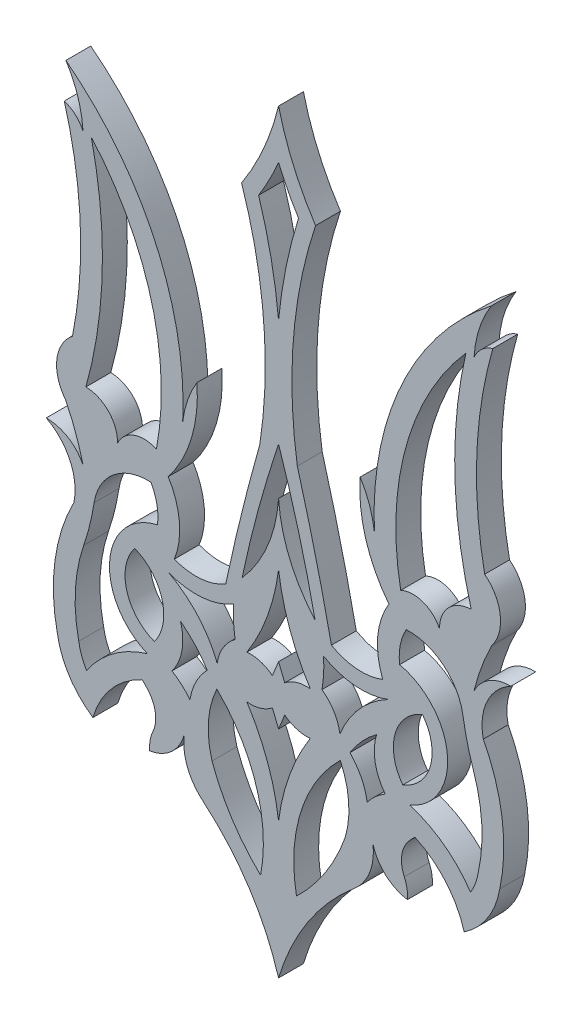
SolidWorks part; units mm, degrees
ref_plane "Спереди" through (0, 0, 0) normal (0, 0, 1) x (1, 0, 0)
ref_plane "Сверху" through (0, 0, 0) normal (0, 1, 0) x (1, 0, 0)
ref_plane "Справа" through (0, 0, 0) normal (1, 0, 0) x (0, 0, -1)
sketch "Эскиз1" plane through (0, 0, 0) normal (0, 0, 1) x (1, 0, 0)
  line L0 (0, 59.3327) -> (0, 0) construction
  line L1 (-37.3731, 0) -> (0, 0) construction
  line L2 (-37.3731, 121.4692) -> (44.9369, 121.4692) construction
  line L3 (-74.7461, 59.3327) -> (-74.7461, -26.1169) construction
  point P4 (0, 0)
  line B0 (-37.3731, 44.06) -> (-38.3679, 41.6166)
  line B1 (-36.3782, 41.6166) -> (-37.3731, 44.06)
  line B2 (-37.3731, 34.6918) -> (-36.3782, 37.1352)
  line B3 (-38.3679, 37.1352) -> (-37.3731, 34.6918)
  arc B4 (-28.8698, 50.6176) -> (-34.3536, 72.8129) centre (-358.3243, -19.0069) ccw
  arc B5 (-28.8698, 50.6176) -> (-20.6106, 49.9659) centre (-24.0648, 58.8518) ccw
  arc B6 (-19.6244, 60.9582) -> (-20.6106, 49.9659) centre (-9.1755, 54.4803) ccw
  arc B7 (-24.2373, 76.3591) -> (-19.6244, 60.9582) centre (-2.0942, 74.6002) ccw
  arc B8 (-21.9542, 69.7913) -> (-24.2373, 76.3591) centre (-38.2708, 67.8) ccw
  arc B9 (-3.1675, 110.7233) -> (-21.9542, 69.7913) centre (26.7273, 72.2251) ccw
  arc B10 (-3.1675, 110.7233) -> (-5.9306, 102.1805) centre (11.9443, 101.1174) ccw
  arc B11 (-2.9051, 104.9263) -> (-5.9306, 102.1805) centre (-1.4532, 100.2868) ccw
  arc B12 (-2.9051, 104.9263) -> (-4.2209, 72.8206) centre (62.502, 86.166) ccw
  arc B13 (-3.1019, 63.4171) -> (-4.2209, 72.8206) centre (-8.3631, 67.5594) ccw
  arc B14 (-3.1019, 63.4171) -> (-5.9412, 55.7096) centre (29.9639, 46.8597) ccw
  arc B15 (0, 59.3327) -> (-5.9412, 55.7096) centre (-0.0966, 52.8084) ccw
  arc B16 (0, 59.3327) -> (-4.4414, 49.7428) centre (4.0617, 51.6282) ccw
  arc B17 (-1.7936, 30.1997) -> (-4.4414, 49.7428) centre (-30.2276, 36.2982) ccw
  arc B18 (-7.516, 21.3534) -> (-1.7936, 30.1997) centre (-14.8478, 32.37) ccw
  arc B19 (-7.516, 21.3534) -> (-15.429, 30.577) centre (-21.5283, 17.3382) ccw
  arc B20 (-15.429, 30.577) -> (-16.5862, 29.3414) centre (-9.8461, 24.1883) ccw
  arc B21 (-16.5862, 29.3414) -> (-17.1526, 24.2063) centre (-12.6141, 26.3045) ccw
  arc B22 (-16.6537, 21.2711) -> (-17.1526, 24.2063) centre (-22.3175, 21.8184) ccw
  arc B23 (-22.2033, 26.3212) -> (-16.6537, 21.2711) centre (-15.5649, 28.042) ccw
  arc B24 (-25.2985, 18.4861) -> (-22.2033, 26.3212) centre (-30.7105, 25.153) ccw
  arc B25 (-25.2985, 18.4861) -> (-37.3731, 0) centre (-0.1868, -11.1026) ccw
  arc B26 (-37.3731, 0) -> (-49.4477, 18.4861) centre (-74.5594, -11.1026) ccw
  arc B27 (-52.5428, 26.3212) -> (-49.4477, 18.4861) centre (-44.0356, 25.153) ccw
  arc B28 (-58.0925, 21.2711) -> (-52.5428, 26.3212) centre (-59.1812, 28.042) ccw
  arc B29 (-57.5936, 24.2063) -> (-58.0925, 21.2711) centre (-52.4287, 21.8184) ccw
  arc B30 (-57.5936, 24.2063) -> (-58.1599, 29.3414) centre (-62.132, 26.3045) ccw
  arc B31 (-58.1599, 29.3414) -> (-59.3172, 30.577) centre (-64.9001, 24.1883) ccw
  arc B32 (-59.3172, 30.577) -> (-67.2302, 21.3534) centre (-53.2178, 17.3382) ccw
  arc B33 (-72.9525, 30.1997) -> (-67.2302, 21.3534) centre (-59.8984, 32.37) ccw
  arc B34 (-70.3048, 49.7428) -> (-72.9525, 30.1997) centre (-44.5186, 36.2982) ccw
  arc B35 (-70.3048, 49.7428) -> (-74.7461, 59.3327) centre (-78.8078, 51.6282) ccw
  arc B36 (-68.805, 55.7096) -> (-74.7461, 59.3327) centre (-74.6496, 52.8084) ccw
  arc B37 (-68.805, 55.7096) -> (-71.6442, 63.4171) centre (-104.7101, 46.8597) ccw
  arc B38 (-70.5253, 72.8206) -> (-71.6442, 63.4171) centre (-66.383, 67.5594) ccw
  arc B39 (-70.5253, 72.8206) -> (-71.841, 104.9263) centre (-137.2482, 86.166) ccw
  arc B40 (-68.8156, 102.1805) -> (-71.841, 104.9263) centre (-73.2929, 100.2868) ccw
  arc B41 (-68.8156, 102.1805) -> (-71.5786, 110.7233) centre (-86.6905, 101.1174) ccw
  arc B42 (-52.7919, 69.7913) -> (-71.5786, 110.7233) centre (-101.4735, 72.2251) ccw
  arc B43 (-50.5088, 76.3591) -> (-52.7919, 69.7913) centre (-36.4754, 67.8) ccw
  arc B44 (-55.1218, 60.9582) -> (-50.5088, 76.3591) centre (-72.6519, 74.6002) ccw
  arc B45 (-54.1355, 49.9659) -> (-55.1218, 60.9582) centre (-65.5706, 54.4803) ccw
  arc B46 (-54.1355, 49.9659) -> (-45.8764, 50.6176) centre (-50.6814, 58.8518) ccw
  arc B47 (-40.3925, 72.8129) -> (-45.8764, 50.6176) centre (283.5782, -19.0069) ccw
  arc B48 (-40.3925, 72.8129) -> (-43.3266, 107.7895) centre (-114.1835, 84.2341) ccw
  arc B49 (-43.3266, 107.7895) -> (-37.3731, 121.4692) centre (-79.608, 131.7148) ccw
  arc B50 (-37.3731, 121.4692) -> (-31.4195, 107.7895) centre (4.8618, 131.7148) ccw
  arc B51 (-31.4195, 107.7895) -> (-34.3536, 72.8129) centre (39.4373, 84.2341) ccw
  arc B52 (-37.3731, 66.8061) -> (-31.506, 52.8203) centre (-14.1375, 68.33) ccw
  arc B53 (-31.506, 52.8203) -> (-37.3731, 74.3776) centre (-219.4365, 13.25) ccw
  arc B54 (-37.3731, 74.3776) -> (-43.2401, 52.8203) centre (144.6903, 13.25) ccw
  arc B55 (-43.2401, 52.8203) -> (-37.3731, 66.8061) centre (-60.6086, 68.33) ccw
  arc B56 (-47.3048, 35.2886) -> (-48.0737, 24.8775) centre (-34.1077, 29.08) ccw
  arc B57 (-48.0737, 24.8775) -> (-40.2595, 12.8543) centre (-18.7569, 35.3804) ccw
  arc B58 (-40.2595, 12.8543) -> (-47.3048, 35.2886) centre (-64.6365, 17.5224) ccw
  arc B59 (-54.5279, 34.2003) -> (-53.141, 41.7989) centre (-61.148, 39.3344) ccw
  arc B60 (-51.6358, 31.6221) -> (-54.5279, 34.2003) centre (-59.5575, 25.6475) ccw
  arc B61 (-48.8542, 37.1352) -> (-51.6358, 31.6221) centre (-41.6113, 30.0225) ccw
  arc B62 (-48.8542, 37.1352) -> (-53.141, 41.7989) centre (-63.2744, 28.1822) ccw
  arc B63 (-55.0413, 47.6358) -> (-44.6164, 48.4584) centre (-50.6814, 58.8518) ccw
  arc B64 (-47.2412, 38.9102) -> (-55.0413, 47.6358) centre (-62.9171, 32.7462) ccw
  arc B65 (-44.3592, 43.665) -> (-47.2412, 38.9102) centre (-40.1531, 37.8647) ccw
  arc B66 (-44.6164, 48.4584) -> (-44.3592, 43.665) centre (-23.5168, 47.1867) ccw
  arc B67 (-57.3499, 36.8835) -> (-60.5177, 48.2841) centre (-63.2682, 41.3795) ccw
  arc B68 (-60.5177, 48.2841) -> (-57.3499, 36.8835) centre (-54.7116, 43.757) ccw
  arc B69 (-58.4641, 34.6364) -> (-68.252, 27.3744) centre (-53.2178, 17.3382) ccw
  arc B70 (-56.845, 53.3859) -> (-58.4641, 34.6364) centre (-54.7116, 43.757) ccw
  arc B71 (-56.845, 53.3859) -> (-57.9102, 58.7991) centre (-65.5706, 54.4803) ccw
  arc B72 (-57.9102, 58.7991) -> (-67.037, 51.3732) centre (-58.3442, 50.0108) ccw
  arc B73 (-68.7166, 44.5943) -> (-67.037, 51.3732) centre (-106.5546, 57.5667) ccw
  arc B74 (-68.7166, 44.5943) -> (-69.5124, 30.8505) centre (-44.5186, 36.2982) ccw
  arc B75 (-69.5124, 30.8505) -> (-68.252, 27.3744) centre (-59.8984, 32.37) ccw
  arc B76 (-57.0175, 63.8261) -> (-67.5018, 102.1048) centre (-101.4735, 72.2251) ccw
  arc B77 (-68.3641, 66.8375) -> (-67.5018, 102.1048) centre (-137.2482, 86.166) ccw
  arc B78 (-63.2682, 61.57) -> (-68.3641, 66.8375) centre (-68.4499, 61.6559) ccw
  arc B79 (-57.0175, 63.8261) -> (-63.2682, 61.57) centre (-59.0149, 59.5727) ccw
  arc B80 (-37.3731, 91.6713) -> (-40.5844, 107.4359) centre (-114.1835, 84.2341) ccw
  arc B81 (-34.1618, 107.4359) -> (-37.3731, 91.6713) centre (39.4373, 84.2341) ccw
  arc B82 (-37.3731, 113.5896) -> (-34.1618, 107.4359) centre (4.8618, 131.7148) ccw
  arc B83 (-40.5844, 107.4359) -> (-37.3731, 113.5896) centre (-79.608, 131.7148) ccw
  arc B84 (-21.6051, 41.7989) -> (-20.2183, 34.2003) centre (-13.5981, 39.3344) ccw
  arc B85 (-21.6051, 41.7989) -> (-25.892, 37.1352) centre (-11.4717, 28.1822) ccw
  arc B86 (-23.1103, 31.6221) -> (-25.892, 37.1352) centre (-33.1348, 30.0225) ccw
  arc B87 (-20.2183, 34.2003) -> (-23.1103, 31.6221) centre (-15.1886, 25.6475) ccw
  arc B88 (-32.2722, 42.8313) -> (-36.3782, 41.6166) centre (-32.8603, 37.2719) ccw
  arc B89 (-37.3731, 56.8888) -> (-32.2722, 42.8313) centre (-3.6942, 61.1553) ccw
  arc B90 (-42.474, 42.8313) -> (-37.3731, 56.8888) centre (-71.0519, 61.1553) ccw
  arc B91 (-38.3679, 41.6166) -> (-42.474, 42.8313) centre (-41.8858, 37.2719) ccw
  arc B92 (-34.4866, 12.8543) -> (-26.6724, 24.8775) centre (-55.9892, 35.3804) ccw
  arc B93 (-26.6724, 24.8775) -> (-27.4413, 35.2886) centre (-40.6385, 29.08) ccw
  arc B94 (-27.4413, 35.2886) -> (-34.4866, 12.8543) centre (-10.1096, 17.5224) ccw
  arc B95 (-36.3782, 37.1352) -> (-32.2722, 35.9206) centre (-32.8603, 41.48) ccw
  arc B96 (-42.474, 35.9206) -> (-38.3679, 37.1352) centre (-41.8858, 41.48) ccw
  arc B97 (-37.3731, 21.863) -> (-42.474, 35.9206) centre (-71.0519, 17.5966) ccw
  arc B98 (-32.2722, 35.9206) -> (-37.3731, 21.863) centre (-3.6942, 17.5966) ccw
  arc B99 (-17.3963, 36.8835) -> (-14.2285, 48.2841) centre (-20.0346, 43.757) ccw
  arc B100 (-14.2285, 48.2841) -> (-17.3963, 36.8835) centre (-11.4779, 41.3795) ccw
  arc B101 (-6.4942, 27.3744) -> (-16.282, 34.6364) centre (-21.5283, 17.3382) ccw
  arc B102 (-6.4942, 27.3744) -> (-5.2337, 30.8505) centre (-14.8478, 32.37) ccw
  arc B103 (-5.2337, 30.8505) -> (-6.0295, 44.5943) centre (-30.2276, 36.2982) ccw
  arc B104 (-7.7091, 51.3732) -> (-6.0295, 44.5943) centre (31.8085, 57.5667) ccw
  arc B105 (-7.7091, 51.3732) -> (-16.8359, 58.7991) centre (-16.402, 50.0108) ccw
  arc B106 (-16.8359, 58.7991) -> (-17.9011, 53.3859) centre (-9.1755, 54.4803) ccw
  arc B107 (-16.282, 34.6364) -> (-17.9011, 53.3859) centre (-20.0346, 43.757) ccw
  arc B108 (-30.1298, 48.4584) -> (-19.7048, 47.6358) centre (-24.0648, 58.8518) ccw
  arc B109 (-30.3869, 43.665) -> (-30.1298, 48.4584) centre (-51.2293, 47.1867) ccw
  arc B110 (-27.5049, 38.9102) -> (-30.3869, 43.665) centre (-34.5931, 37.8647) ccw
  arc B111 (-19.7048, 47.6358) -> (-27.5049, 38.9102) centre (-11.829, 32.7462) ccw
  arc B112 (-11.4779, 61.57) -> (-17.7286, 63.8261) centre (-15.7313, 59.5727) ccw
  arc B113 (-6.382, 66.8375) -> (-11.4779, 61.57) centre (-6.2962, 61.6559) ccw
  arc B114 (-7.2444, 102.1048) -> (-6.382, 66.8375) centre (62.502, 86.166) ccw
  arc B115 (-7.2444, 102.1048) -> (-17.7286, 63.8261) centre (26.7273, 72.2251) ccw
  dimension "D1" = 121.4692
  dimension "D2" = 74.7461
sketch_block_instance "Блок1-1"
sketch_block "Блок1"
extrude "Бобышка-Вытянуть1" add sketch "Эскиз1" along normal blind 4
scale "Масштаб1" scale about centroid uniform scaling yes scale factor 0.5
